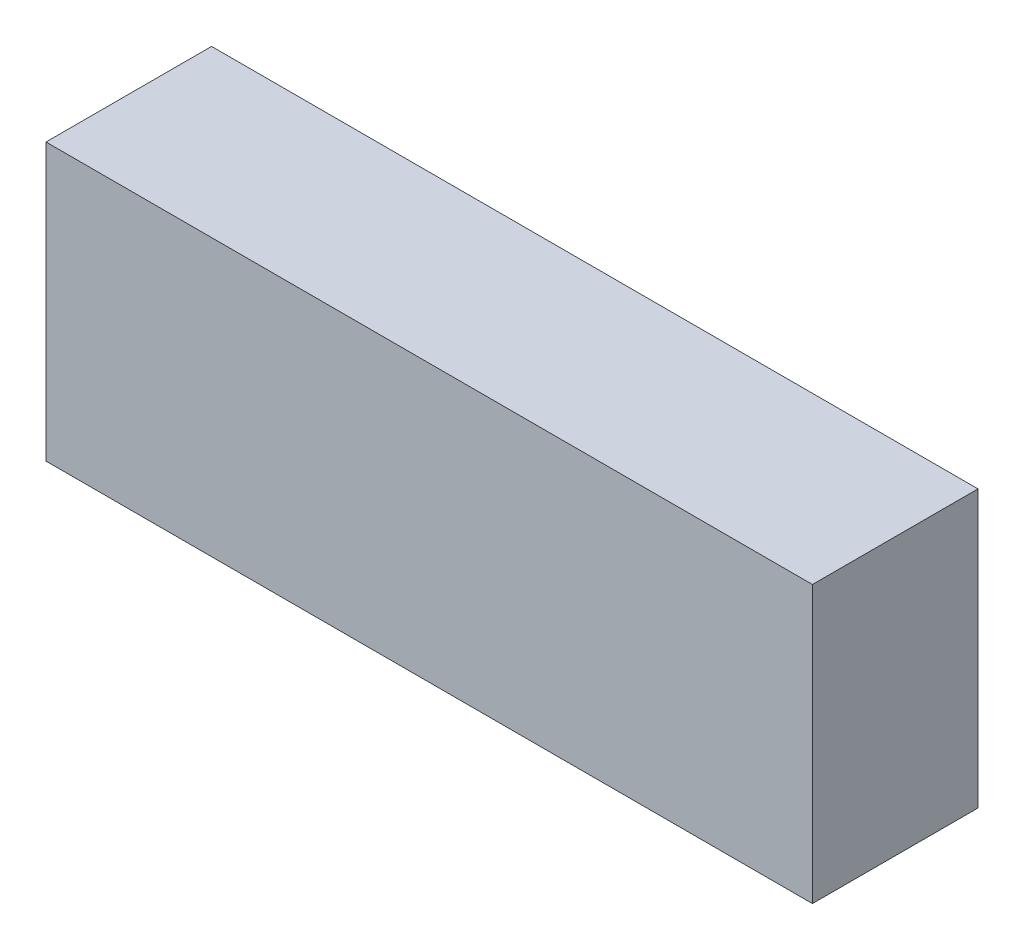
SolidWorks part; units mm, degrees
ref_plane "Front Plane" through (0, 0, 0) normal (0, 0, 1) x (1, 0, 0)
ref_plane "Top Plane" through (0, 0, 0) normal (0, 1, 0) x (1, 0, 0)
ref_plane "Right Plane" through (0, 0, 0) normal (1, 0, 0) x (0, 0, -1)
sketch "Sketch1" plane through (0, 0, 0) normal (0, 0, 1) x (1, 0, 0)
  line L0 (29.3045, 77.7714) -> (-4.6555, 77.7714) construction
  line L1 (-4.4555, 77.5714) -> (29.1045, 77.5714)
  line L2 (-4.4555, 77.5714) -> (-4.4555, 65.47)
  line L3 (-4.4555, 65.47) -> (29.1045, 65.47)
  line L4 (29.1045, 77.5714) -> (29.1045, 65.47)
  line L5 (29.3045, 77.7714) -> (29.3045, 65.27) construction
  line L6 (29.3045, 65.27) -> (-4.6555, 65.27) construction
  line L7 (-4.6555, 65.27) -> (-4.6555, 77.7714) construction
  dimension "D1" = 0.2
  dimension "D2" = 0.2
  dimension "D3" = 0.2
  dimension "D4" = 0.2
extrude "Boss-Extrude1" add sketch "Sketch1" along normal blind 7.25 contours L1 L4 L3 L2
shell "Shell1" thickness 0.5
equation "\"D3@Sketch1\"=\"D1@Sketch1\""
equation "\"D2@Sketch1\"=\"D1@Sketch1\""
equation "\"D4@Sketch1\"=\"D1@Sketch1\""
